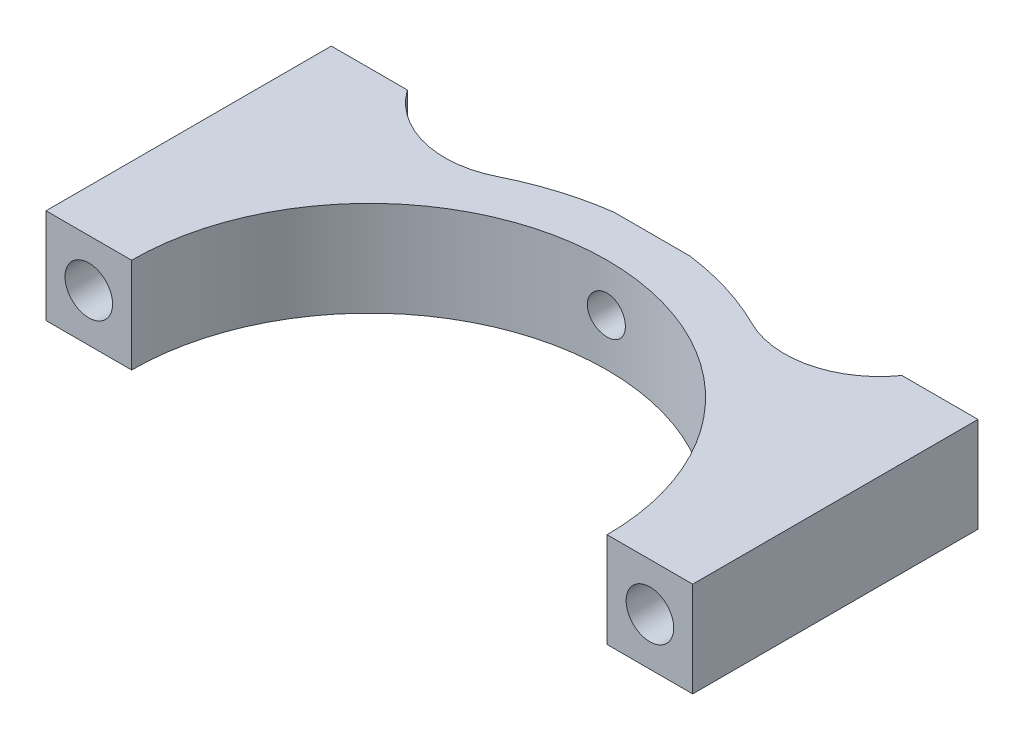
SolidWorks part; units mm, degrees
ref_plane "前视基准面" through (0, 0, 0) normal (0, 0, 1) x (1, 0, 0)
ref_plane "上视基准面" through (0, 0, 0) normal (0, 1, 0) x (1, 0, 0)
ref_plane "右视基准面" through (0, 0, 0) normal (1, 0, 0) x (0, 0, -1)
other "Configuration Table"
sketch "草图1" plane through (0, 0, 0) normal (0, 1, 0) x (1, 0, 0)
  line L0 (-25, 0) -> (-34, 0)
  line L1 (-34, 0) -> (-34, 30)
  line L2 (0, 0) -> (0, 44.0834) construction
  line L3 (-34, 30) -> (-26, 30)
  line L4 (-4, 29.7321) -> (4, 29.7321)
  line L5 (34, 30) -> (26, 30)
  line L6 (25, 0) -> (34, 0)
  line L7 (34, 0) -> (34, 30)
  circle A0 centre (0, 0) radius 25 construction
  circle A1 centre (0, 0) radius 30 construction
  arc A2 (-26, 30) -> (-13.3882, 26.8469) centre (-17.8509, 35.7959) ccw
  arc A3 (-13.3882, 26.8469) -> (-4, 29.7321) centre (0, 0) cw
  arc A4 (-25, 0) -> (25, 0) centre (0, 0) cw
  arc A5 (13.3882, 26.8469) -> (4, 29.7321) centre (0, 0) ccw
  arc A6 (26, 30) -> (13.3882, 26.8469) centre (17.8509, 35.7959) cw
  point P19 (0, 29.7321)
  dimension "D1" = 50
  dimension "D6" = 8
  dimension "D7" = 10
  dimension "D3" = 34
  dimension "D4" = 30
  dimension "D5" = 4
  dimension "D2" = 5
extrude "凸台-拉伸1" add sketch "草图1" along normal blind 10
sketch "草图2" plane through (0, 0, -30) normal (0, 0, -1) x (-1, 0, 0)
  line L0 (-34, 5) -> (34, 5) construction
  line L1 (-34, 10) -> (-34, 0) construction
  line L2 (34, 10) -> (34, 0) construction
  line L3 (0, 0) -> (0, 22.8433) construction
  circle A0 centre (-29.5, 5) radius 2.5
  circle A1 centre (29.5, 5) radius 2.5
  circle A2 centre (0, 5) radius 2
  dimension "D1" = 5
  dimension "D2" = 59
  dimension "D3" = 4
extrude "切除-拉伸1" cut sketch "草图2" against normal blind 40
